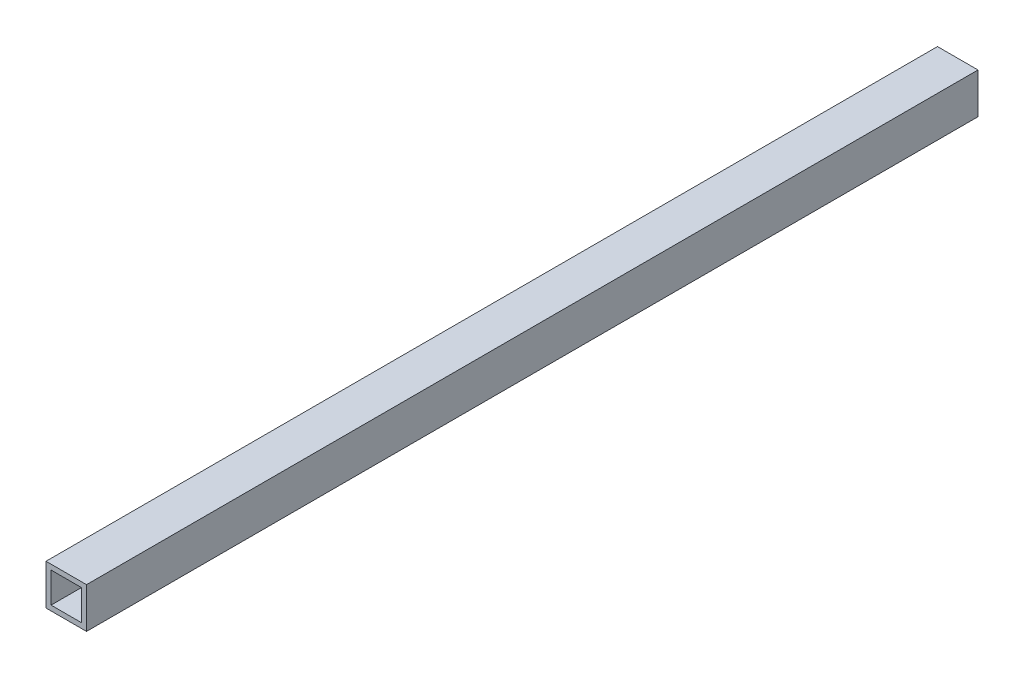
SolidWorks part; units mm, degrees
ref_plane "Front Plane" through (0, 0, 0) normal (0, 0, 1) x (1, 0, 0)
ref_plane "Top Plane" through (0, 0, 0) normal (0, 1, 0) x (1, 0, 0)
ref_plane "Right Plane" through (0, 0, 0) normal (1, 0, 0) x (0, 0, -1)
sketch "Sketch1" plane through (0, 0, 0) normal (0, 0, 1) x (1, 0, 0)
  line L5 (12.7, 12.7) -> (-12.7, 12.7)
  line L6 (12.7, 12.7) -> (12.7, -12.7)
  line L7 (12.7, -12.7) -> (-12.7, -12.7)
  line L8 (-12.7, 12.7) -> (-12.7, -12.7)
  line L9 (12.7, 12.7) -> (-12.7, -12.7) construction
  line L10 (12.7, -12.7) -> (-12.7, 12.7) construction
  line L15 (9.525, 9.525) -> (-9.525, 9.525)
  line L16 (9.525, 9.525) -> (9.525, -9.525)
  line L17 (9.525, -9.525) -> (-9.525, -9.525)
  line L18 (-9.525, 9.525) -> (-9.525, -9.525)
  line L19 (9.525, 9.525) -> (-9.525, -9.525) construction
  line L20 (9.525, -9.525) -> (-9.525, 9.525) construction
  point P0 (0, 0)
  point P6 (0, 0)
  dimension "D1" = 3.175
  dimension "D2" = 25.4
  dimension "D3" = 25.4
extrude "Boss-Extrude1" add sketch "Sketch1" along normal blind 558.8
